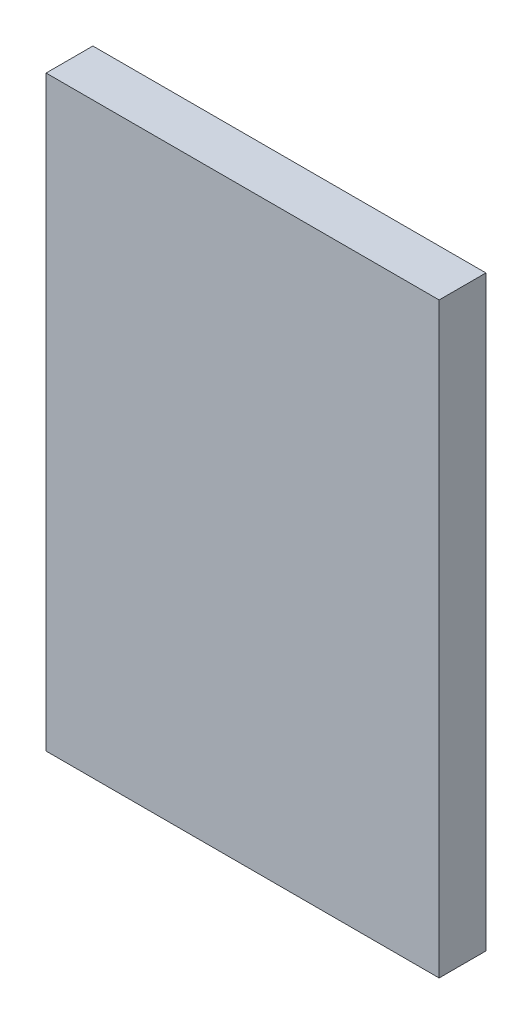
SolidWorks part; units mm, degrees
ref_plane "Front Plane" through (0, 0, 0) normal (0, 0, 1) x (1, 0, 0)
ref_plane "Top Plane" through (0, 0, 0) normal (0, 1, 0) x (1, 0, 0)
ref_plane "Right Plane" through (0, 0, 0) normal (1, 0, 0) x (0, 0, -1)
sketch "Sketch1" plane through (0, 0, 0) normal (0, 0, 1) x (1, 0, 0)
  line L1 (0, 0) -> (42.672, 0)
  line L2 (0, 0) -> (0, 63.754)
  line L3 (0, 63.754) -> (42.672, 63.754)
  line L4 (42.672, 0) -> (42.672, 63.754)
  dimension "D1" = 42.672
  dimension "D2" = 63.754
extrude "Boss-Extrude1" add sketch "Sketch1" along normal blind 5.08
